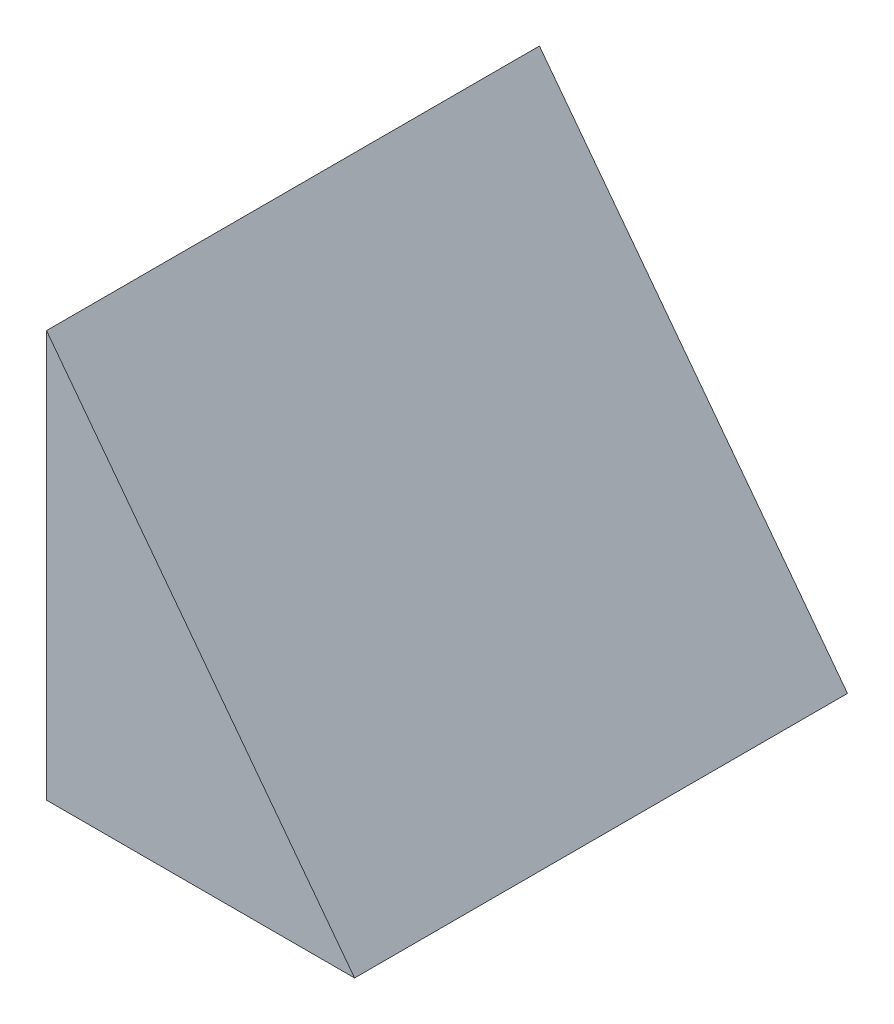
SolidWorks part; units mm, degrees
ref_plane "Front Plane" through (0, 0, 0) normal (0, 0, 1) x (1, 0, 0)
ref_plane "Top Plane" through (0, 0, 0) normal (0, 1, 0) x (1, 0, 0)
ref_plane "Right Plane" through (0, 0, 0) normal (1, 0, 0) x (0, 0, -1)
sketch "Sketch1" plane through (0, 0, 0) normal (0, 0, 1) x (1, 0, 0)
  line L0 (0, 0) -> (0, 838.2)
  line L1 (0, 838.2) -> (635, 0)
  line L2 (635, 0) -> (0, 0)
  dimension "D1" = 838.2
  dimension "D2" = 635
extrude "Boss-Extrude1" add sketch "Sketch1" against normal blind 1016
